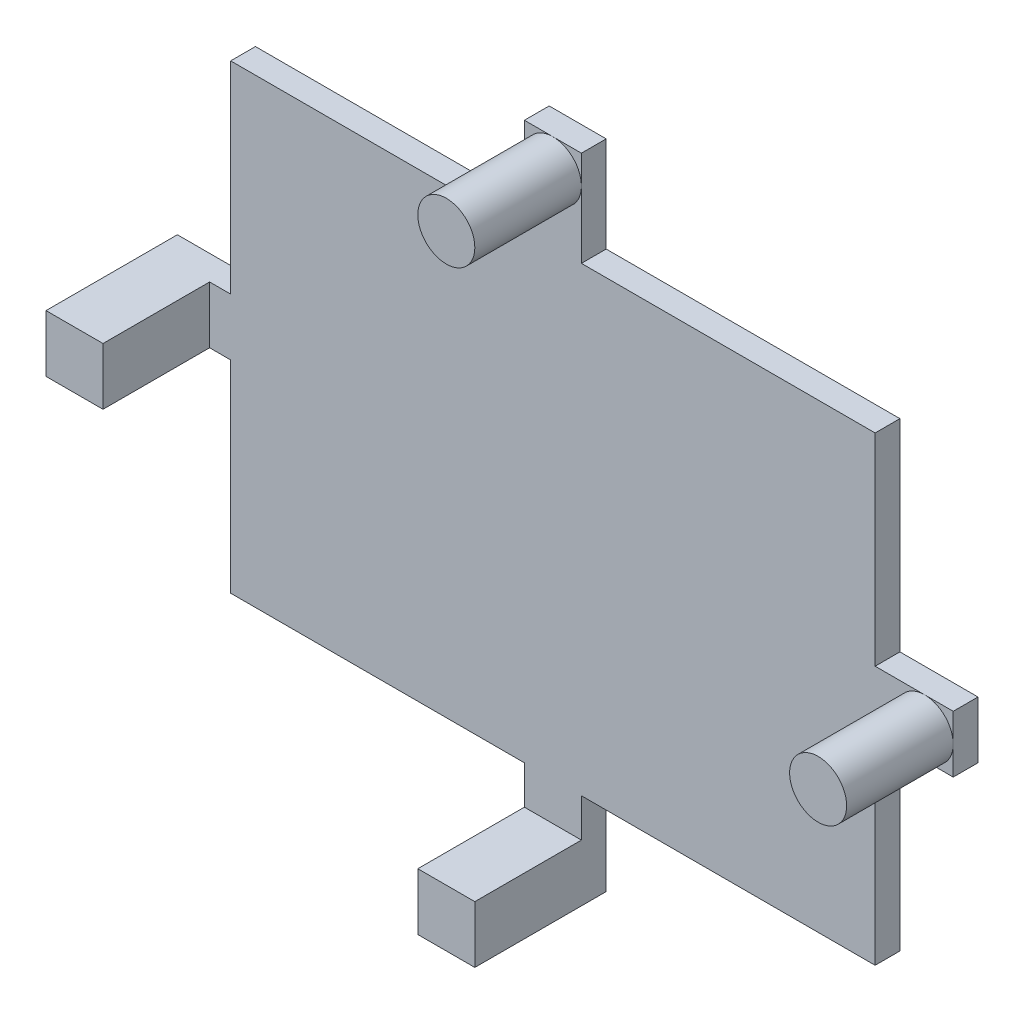
SolidWorks part; units mm, degrees
ref_plane "Front Plane" through (0, 0, 0) normal (0, 0, 1) x (1, 0, 0)
ref_plane "Top Plane" through (0, 0, 0) normal (0, 1, 0) x (1, 0, 0)
ref_plane "Right Plane" through (0, 0, 0) normal (1, 0, 0) x (0, 0, -1)
sketch "Sketch1" plane through (0, 0, 0) normal (0, 0, 1) x (1, 0, 0)
  line L1 (-65, -46.5) -> (65, -46.5)
  line L2 (-65, -46.5) -> (-65, 46.5)
  line L3 (-65, 46.5) -> (65, 46.5)
  line L4 (65, -46.5) -> (65, 46.5)
  line L5 (-65, -46.5) -> (65, 46.5) construction
  line L6 (-65, 46.5) -> (65, -46.5) construction
  point P0 (0, 0)
  dimension "D1" = 130
  dimension "D2" = 93
extrude "Boss-Extrude1" add sketch "Sketch1" along normal blind 5
sketch "Sketch2" plane through (0, 0, 5) normal (0, 0, 1) x (1, 0, 0)
  line L0 (0, 0) -> (-75, 0)
  line L1 (0, 0) -> (75, 0)
  line L2 (0, 0) -> (0, 60)
  line L3 (0, 0) -> (0, -60)
  line L5 (-80.75, 5.75) -> (-69.25, 5.75)
  line L6 (-80.75, 5.75) -> (-80.75, -5.75)
  line L7 (-80.75, -5.75) -> (-69.25, -5.75)
  line L8 (-69.25, 5.75) -> (-69.25, -5.75)
  line L9 (-80.75, 5.75) -> (-69.25, -5.75) construction
  line L10 (-80.75, -5.75) -> (-69.25, 5.75) construction
  line L17 (-5.75, -65.75) -> (5.75, -65.75)
  line L18 (-5.75, -65.75) -> (-5.75, -54.25)
  line L19 (-5.75, -54.25) -> (5.75, -54.25)
  line L20 (5.75, -65.75) -> (5.75, -54.25)
  line L21 (-5.75, -65.75) -> (5.75, -54.25) construction
  line L22 (-5.75, -54.25) -> (5.75, -65.75) construction
  circle A0 centre (0, 60) radius 5.75
  circle A2 centre (75, 0) radius 5.75
  dimension "D7" = 11.5
  dimension "D8" = 11.5
  dimension "D5" = 11.5
  dimension "D1" = 75
  dimension "75 mm" = 75
  dimension "D2" = 60
  dimension "0" = 60
  dimension "D3" = 11.5
  dimension "D4" = 11.5
extrude "Boss-Extrude2" add sketch "Sketch2" along normal blind 21.5 separate body
sketch "Sketch3" plane through (0, 0, 0) normal (0, 0, -1) x (-1, 0, 0)
  line L1 (-80.75, -5.75) -> (80.75, -5.75)
  line L2 (-80.75, -5.75) -> (-80.75, 5.75)
  line L3 (-80.75, 5.75) -> (80.75, 5.75)
  line L4 (80.75, -5.75) -> (80.75, 5.75)
  line L5 (-80.75, -5.75) -> (80.75, 5.75) construction
  line L6 (-80.75, 5.75) -> (80.75, -5.75) construction
  line L7 (-5.75, 65.75) -> (5.75, 65.75)
  line L8 (-5.75, 65.75) -> (-5.75, -65.75)
  line L9 (-5.75, -65.75) -> (5.75, -65.75)
  line L10 (5.75, 65.75) -> (5.75, -65.75)
  line L11 (-5.75, 65.75) -> (5.75, -65.75) construction
  line L12 (-5.75, -65.75) -> (5.75, 65.75) construction
  point P0 (0, 0)
  point P7 (0, 0)
  line M1 (-65, 46.5) -> (-65, -46.5)
  line M2 (-65, -46.5) -> (65, -46.5)
  line M3 (65, -46.5) -> (65, 46.5)
  line M4 (65, 46.5) -> (-65, 46.5)
extrude "Boss-Extrude3" add sketch "Sketch3" against normal up to surface (5 mm away) contours L10 L7 L8 M4 | L3 L2 L1 M1 | L10 L8 L9 M2 | L1 L4 L3 M3 up to face at (80.75, 0, 5)
